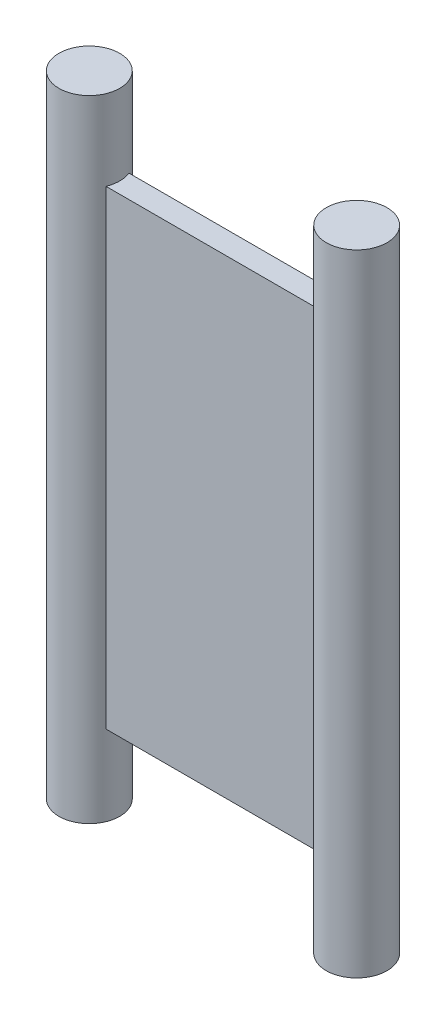
SolidWorks part; units mm, degrees
ref_plane "Front Plane" through (0, 0, 0) normal (0, 0, 1) x (1, 0, 0)
ref_plane "Top Plane" through (0, 0, 0) normal (0, 1, 0) x (1, 0, 0)
ref_plane "Right Plane" through (0, 0, 0) normal (1, 0, 0) x (0, 0, -1)
sketch "Sketch1" plane through (0, 0, 0) normal (0, 1, 0) x (1, 0, 0)
  line L1 (5.83, 0.5) -> (-5.83, 0.5)
  line L2 (5.83, 0.5) -> (5.83, -0.5)
  line L3 (5.83, -0.5) -> (-5.83, -0.5)
  line L4 (-5.83, 0.5) -> (-5.83, -0.5)
  line L5 (5.83, 0.5) -> (-5.83, -0.5) construction
  line L6 (5.83, -0.5) -> (-5.83, 0.5) construction
  point P0 (0, 0)
  dimension "D1" = 11.66
  dimension "D3" = 1
extrude "Boss-Extrude1" add sketch "Sketch1" along normal blind 20.5
ref_plane "Plane1" through (0, 10.25, 0) normal (0, 1, 0) x (1, 0, 0)
sketch "Sketch2" plane through (0, 10.25, 0) normal (0, 1, 0) x (1, 0, 0)
  line L0 (5.83, -0.5) -> (5.83, 0.5) construction
  line L1 (-5.83, 0.5) -> (-5.83, -0.5) construction
  line L2 (5.83, -0.5) -> (5.83, 0.5) construction
  line L3 (-5.83, 0.5) -> (-5.83, -0.5) construction
  circle A0 centre (-5.83, 0) radius 1.325
  circle A1 centre (5.83, 0) radius 1.325
  dimension "D1" = 2.65
extrude "Boss-Extrude2" add sketch "Sketch2" along normal mid plane 27.5
